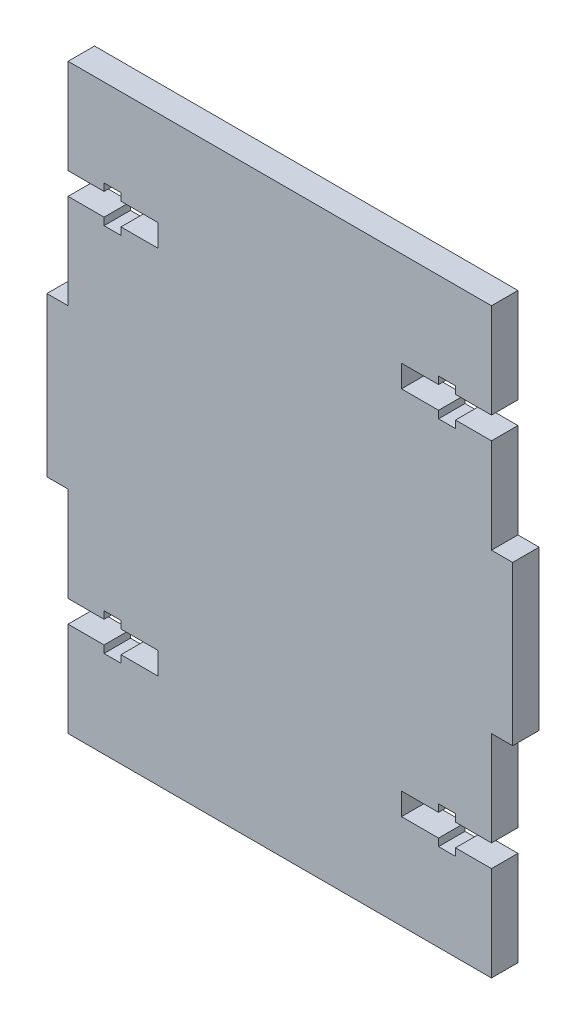
SolidWorks part; units mm, degrees
material "Balsa"
ref_plane "Plan de face" through (0, 0, 0) normal (0, 0, 1) x (1, 0, 0)
ref_plane "Plan de dessus" through (0, 0, 0) normal (0, 1, 0) x (1, 0, 0)
ref_plane "Plan de droite" through (0, 0, 0) normal (1, 0, 0) x (0, 0, -1)
sketch "Esquisse1" plane through (0, 0, 0) normal (0, 0, 1) x (1, 0, 0)
  line L1 (0, 0) -> (-80, 0)
  line L2 (0, 0) -> (0, 110)
  line L3 (0, 110) -> (-80, 110)
  line L4 (-80, 0) -> (-80, 110)
  dimension "D1" = 80
  dimension "D2" = 110
extrude "Boss.-Extru.1" add sketch "Esquisse1" along normal blind 5
sketch "Esquisse3" plane through (0, 0, 5) normal (0, 0, 1) x (1, 0, 0)
  line L0 (-40, 110) -> (-40, 0) construction
  line L1 (0, 110) -> (-80, 110) construction
  line L3 (-80, 55) -> (0, 55) construction
  line L4 (-80, 110) -> (-80, 0) construction
  line L5 (0, 0) -> (0, 110) construction
  line L6 (-80, 87.9) -> (-80, 92.1)
  line L7 (-80, 92.1) -> (-73.2, 92.1)
  line L8 (-73.2, 92.1) -> (-73.2, 93.5)
  line L9 (-73.2, 93.5) -> (-70, 93.5)
  line L11 (-70, 87.9) -> (-63, 87.9)
  line L12 (-63, 87.9) -> (-63, 92.1)
  line L13 (-63, 90) -> (-80, 90) construction
  line L14 (-80, 87.9) -> (-73.2, 87.9)
  line L15 (-73.2, 87.9) -> (-73.2, 86.5)
  line L16 (-73.2, 86.5) -> (-70, 86.5)
  line L18 (-70, 92.1) -> (-63, 92.1)
  line L19 (-70, 92.1) -> (-70, 93.5)
  line L20 (-70, 86.5) -> (-70, 87.9)
  line L21 (-70, 87.9) -> (-63, 87.9)
  line L22 (-73.2, 93.5) -> (-70, 93.5)
  line L23 (-73.2, 92.1) -> (-73.2, 93.5)
  line L24 (-80, 92.1) -> (-73.2, 92.1)
  line L25 (-70, 92.1) -> (-63, 92.1)
  line L26 (-73.2, 86.5) -> (-70, 86.5)
  line L27 (-73.2, 87.9) -> (-73.2, 86.5)
  line L28 (-80, 87.9) -> (-73.2, 87.9)
  line L29 (-17, 90) -> (0, 90) construction
  line L30 (-10, 87.9) -> (-10, 86.5)
  line L31 (-10, 93.5) -> (-10, 92.1)
  line L32 (0, 87.9) -> (-6.8, 87.9)
  line L33 (-6.8, 87.9) -> (-6.8, 86.5)
  line L34 (-6.8, 86.5) -> (-10, 86.5)
  line L35 (-10, 92.1) -> (-17, 92.1)
  line L36 (0, 92.1) -> (-6.8, 92.1)
  line L37 (-6.8, 92.1) -> (-6.8, 93.5)
  line L38 (-6.8, 93.5) -> (-10, 93.5)
  line L39 (-10, 87.9) -> (-17, 87.9)
  line L40 (-10, 86.5) -> (-10, 87.9)
  line L41 (-10, 92.1) -> (-10, 93.5)
  line L42 (-10, 92.1) -> (-17, 92.1)
  line L43 (-6.8, 86.5) -> (-10, 86.5)
  line L44 (-6.8, 87.9) -> (-6.8, 86.5)
  line L45 (0, 87.9) -> (-6.8, 87.9)
  line L46 (-17, 87.9) -> (-17, 92.1)
  line L47 (-10, 87.9) -> (-17, 87.9)
  line L48 (-6.8, 93.5) -> (-10, 93.5)
  line L49 (-6.8, 92.1) -> (-6.8, 93.5)
  line L50 (0, 92.1) -> (-6.8, 92.1)
  line L51 (0, 87.9) -> (0, 92.1)
  line L52 (-17, 20) -> (0, 20) construction
  line L53 (-63, 20) -> (-80, 20) construction
  line L54 (-70, 22.1) -> (-70, 23.5)
  line L55 (-70, 16.5) -> (-70, 17.9)
  line L56 (0, 22.1) -> (0, 17.9)
  line L57 (0, 17.9) -> (-6.8, 17.9)
  line L58 (-70, 93.5) -> (-70, 92.1)
  line L59 (-70, 87.9) -> (-70, 86.5)
  line L60 (-6.8, 17.9) -> (-6.8, 16.5)
  line L61 (-6.8, 16.5) -> (-10, 16.5)
  line L62 (-10, 22.1) -> (-17, 22.1)
  line L63 (-17, 22.1) -> (-17, 17.9)
  line L64 (0, 22.1) -> (-6.8, 22.1)
  line L65 (-6.8, 22.1) -> (-6.8, 23.5)
  line L66 (-6.8, 23.5) -> (-10, 23.5)
  line L67 (-10, 17.9) -> (-17, 17.9)
  line L68 (-10, 17.9) -> (-10, 16.5)
  line L69 (-10, 23.5) -> (-10, 22.1)
  line L70 (-10, 22.1) -> (-17, 22.1)
  line L71 (-6.8, 16.5) -> (-10, 16.5)
  line L72 (-6.8, 17.9) -> (-6.8, 16.5)
  line L73 (0, 17.9) -> (-6.8, 17.9)
  line L74 (-10, 17.9) -> (-17, 17.9)
  line L75 (-6.8, 23.5) -> (-10, 23.5)
  line L76 (-6.8, 22.1) -> (-6.8, 23.5)
  line L77 (0, 22.1) -> (-6.8, 22.1)
  line L78 (-10, 16.5) -> (-10, 17.9)
  line L79 (-10, 22.1) -> (-10, 23.5)
  line L80 (-80, 22.1) -> (-73.2, 22.1)
  line L81 (-73.2, 22.1) -> (-73.2, 23.5)
  line L82 (-73.2, 23.5) -> (-70, 23.5)
  line L83 (-70, 17.9) -> (-63, 17.9)
  line L84 (-80, 17.9) -> (-73.2, 17.9)
  line L85 (-73.2, 17.9) -> (-73.2, 16.5)
  line L86 (-73.2, 16.5) -> (-70, 16.5)
  line L87 (-70, 22.1) -> (-63, 22.1)
  line L88 (-70, 23.5) -> (-70, 22.1)
  line L89 (-70, 17.9) -> (-70, 16.5)
  line L90 (-70, 17.9) -> (-63, 17.9)
  line L91 (-73.2, 23.5) -> (-70, 23.5)
  line L92 (-73.2, 22.1) -> (-73.2, 23.5)
  line L93 (-80, 22.1) -> (-73.2, 22.1)
  line L94 (-63, 22.1) -> (-63, 17.9)
  line L95 (-70, 22.1) -> (-63, 22.1)
  line L96 (-73.2, 16.5) -> (-70, 16.5)
  line L97 (-73.2, 17.9) -> (-73.2, 16.5)
  line L98 (-80, 17.9) -> (-73.2, 17.9)
  line L99 (-80, 22.1) -> (-80, 17.9)
  line L100 (-80, 0) -> (0, 0) construction
  line M16 (0, 0) -> (0, 110)
  line M18 (-80, 110) -> (-80, 0)
  dimension "D1" = 4.2
  dimension "D2" = 7
  dimension "D3" = 3.2
  dimension "D4" = 10
  dimension "D5" = 20
  dimension "D6" = 17
extrude "Enlèv. mat.-Extru.2" cut sketch "Esquisse3" against normal through all contours L46 L39 L30 L34 L33 L32 L36 L37 L38 L31 L35 M16 | L16 L20 L11 L12 L18 L19 L9 L8 L7 L14 L15 M18 | L94 L87 L54 L82 L81 L80 L84 L85 L86 L55 L83 M18 | L66 L69 L62 L63 L67 L68 L61 L60 L57 L64 L65 M16
sketch "Esquisse4" plane through (0, 0, 0) normal (0, 0, -1) x (-1, 0, 0)
  line L0 (63, 87.9) -> (63, 92.1) construction
  line L5 (80, 55) -> (0, 55) construction
  line L6 (0, 22.1) -> (0, 87.9) construction
  line L7 (0, 22.1) -> (0, 87.9) construction
  line L8 (40, 0) -> (40, 55) construction
  line L9 (80, 0) -> (0, 0) construction
  line L15 (-4, 70) -> (84, 70)
  line L16 (-4, 70) -> (-4, 40)
  line L17 (-4, 40) -> (84, 40)
  line L18 (84, 70) -> (84, 40)
  line L19 (84, 50) -> (84, 77.9) construction
  point P5 (84, 55)
  point P23 (63, 90)
  dimension "D1" = 20
  dimension "D2" = 4
extrude "Boss.-Extru.2" add sketch "Esquisse4" against normal blind 5
